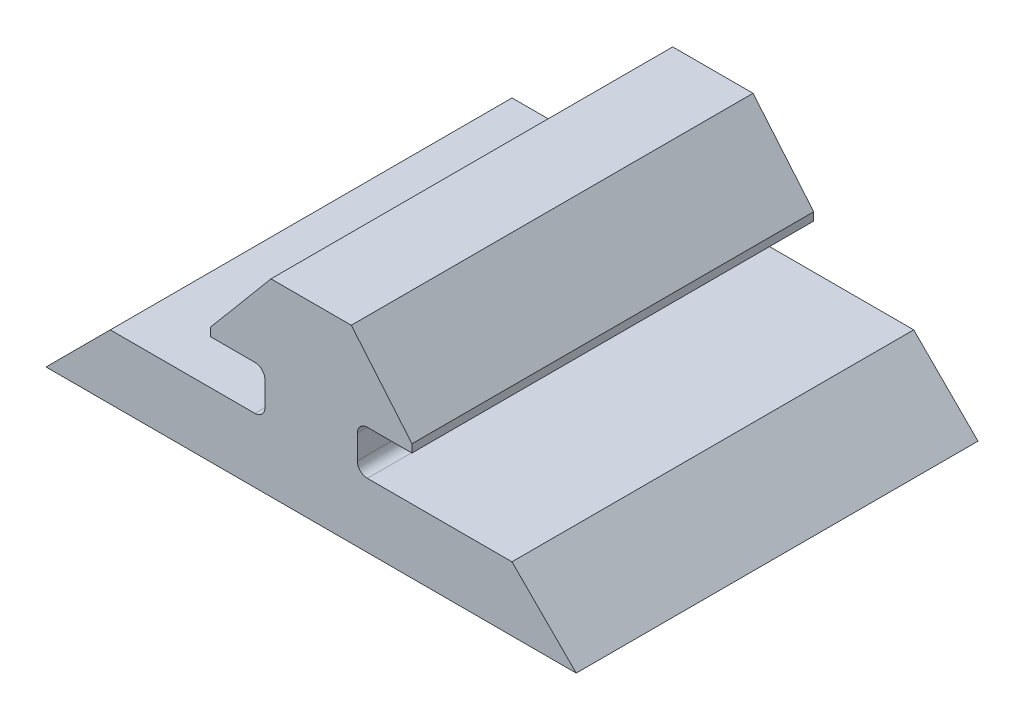
SolidWorks part; units mm, degrees
ref_plane "Front Plane" through (0, 0, 0) normal (0, 0, 1) x (1, 0, 0)
ref_plane "Top Plane" through (0, 0, 0) normal (0, 1, 0) x (1, 0, 0)
ref_plane "Right Plane" through (0, 0, 0) normal (1, 0, 0) x (0, 0, -1)
ref_plane "Plane1" through (0, 0, -3683) normal (0, 0, -1) x (-1, 0, 0)
sketch "Sketch1" plane through (0, 0, -3683) normal (0, 0, -1) x (-1, 0, 0)
  line L0 (12.7, 4.064) -> (3.556, 4.064)
  line L1 (2.921, 4.699) -> (2.921, 6.223)
  line L2 (3.556, 6.858) -> (6.3764, 6.858)
  line L3 (6.3764, 6.858) -> (6.3764, 7.366)
  line L4 (6.3764, 7.366) -> (2.54, 11.938)
  line L5 (2.54, 11.938) -> (-2.54, 11.938)
  line L6 (-2.54, 11.938) -> (-6.3764, 7.366)
  line L7 (-6.3764, 7.366) -> (-6.3764, 6.858)
  line L8 (-6.3764, 6.858) -> (-3.556, 6.858)
  line L9 (-2.921, 6.223) -> (-2.921, 4.699)
  line L10 (-3.556, 4.064) -> (-12.7, 4.064)
  line L11 (-12.7, 4.064) -> (-12.7, 0)
  line L12 (-12.7, 0) -> (12.7, 0)
  line L13 (12.7, 0) -> (12.7, 4.064)
  arc A0 (3.556, 4.064) -> (2.921, 4.699) centre (3.556, 4.699) cw
  arc A1 (2.921, 6.223) -> (3.556, 6.858) centre (3.556, 6.223) cw
  arc A2 (-3.556, 6.858) -> (-2.921, 6.223) centre (-3.556, 6.223) cw
  arc A3 (-2.921, 4.699) -> (-3.556, 4.064) centre (-3.556, 4.699) cw
extrude "Boss-Extrude1" add sketch "Sketch1" against normal blind 3683
sketch "Sketch2" plane through (0, 0, 0) normal (0, 0, 1) x (1, 0, 0)
  line L0 (12.7, 4.064) -> (38.1, 4.064)
  line L1 (12.7, 4.064) -> (12.7, 0)
  line L2 (12.7, 0) -> (38.1, 0)
  line L3 (38.1, 4.064) -> (38.1, 0)
extrude "Boss-Extrude2" add sketch "Sketch2" against normal blind 50.8
sketch "Sketch3" plane through (0, 4.064, 0) normal (0, 1, 0) x (-1, 0, 0)
  line L0 (-12.7, -50.8) -> (12.7, -50.8)
  line L1 (-12.7, -50.8) -> (-12.7, -3683)
  line L2 (-12.7, -3683) -> (12.7, -3683)
  line L3 (12.7, -50.8) -> (12.7, -3683)
extrude "Cut-Extrude1" cut sketch "Sketch3" against normal blind 50.8
sketch "Sketch4" plane through (0, 11.938, 0) normal (0, 1, 0) x (-1, 0, 0)
  line L0 (6.3764, -50.8) -> (-6.3764, -50.8)
  line L1 (6.3764, -50.8) -> (6.3764, -3683)
  line L2 (6.3764, -3683) -> (-6.3764, -3683)
  line L3 (-6.3764, -50.8) -> (-6.3764, -3683)
extrude "Cut-Extrude2" cut sketch "Sketch4" against normal blind 50.8
sketch "Sketch5" plane through (0, 0, 0) normal (0, 0, 1) x (1, 0, 0)
  line L0 (-12.7, 0) -> (-38.1, 0)
  line L1 (-12.7, 0) -> (-12.7, 4.064)
  line L2 (-12.7, 4.064) -> (-38.1, 4.064)
  line L3 (-38.1, 0) -> (-38.1, 4.064)
extrude "Boss-Extrude3" add sketch "Sketch5" against normal up to surface (50.8 mm away) up to face at (2.8222, 5.7856, -50.8)
sketch "Sketch6" plane through (0, 0, 0) normal (0, 0, 1) x (1, 0, 0)
  line L0 (-38.1, 4.064) -> (-12.7, 4.064)
  line L1 (-38.1, 4.064) -> (-38.1, 0)
  line L2 (-38.1, 0) -> (-12.7, 0)
  line L3 (-12.7, 4.064) -> (-12.7, 0)
extrude "Cut-Extrude3" cut sketch "Sketch6" against normal through all
sketch "Sketch7" plane through (0, 0, 0) normal (0, 0, 1) x (1, 0, 0)
  line L0 (38.1, 0) -> (12.7, 0)
  line L1 (38.1, 0) -> (38.1, 4.064)
  line L2 (38.1, 4.064) -> (12.7, 4.064)
  line L3 (12.7, 0) -> (12.7, 4.064)
extrude "Cut-Extrude4" cut sketch "Sketch7" against normal through all
sketch "Sketch8" plane through (0, 0, 0) normal (0, 0, 1) x (1, 0, 0)
  line L0 (12.7, 4.064) -> (16.764, 0)
  line L1 (16.764, 0) -> (12.7, 0)
  line L2 (12.7, 0) -> (12.7, 4.064)
extrude "Boss-Extrude4" add sketch "Sketch8" against normal through all
sketch "Sketch9" plane through (0, 0, 0) normal (0, 0, 1) x (1, 0, 0)
  line L0 (-12.7, 4.064) -> (-16.764, 0)
  line L1 (-16.764, 0) -> (-12.7, 0)
  line L2 (-12.7, 0) -> (-12.7, 4.064)
extrude "Boss-Extrude5" add sketch "Sketch9" against normal through all
sketch "Sketch10" plane through (0, 0, 0) normal (0, -1, 0) x (1, 0, 0)
  line L0 (16.764, -50.8) -> (-16.764, -50.8)
  line L1 (16.764, -50.8) -> (16.764, -25.4032)
  line L2 (16.764, -25.4032) -> (-16.764, -25.4032)
  line L3 (-16.764, -50.8) -> (-16.764, -25.4032)
extrude "Cut-Extrude5" cut sketch "Sketch10" against normal through all and the other way through all
